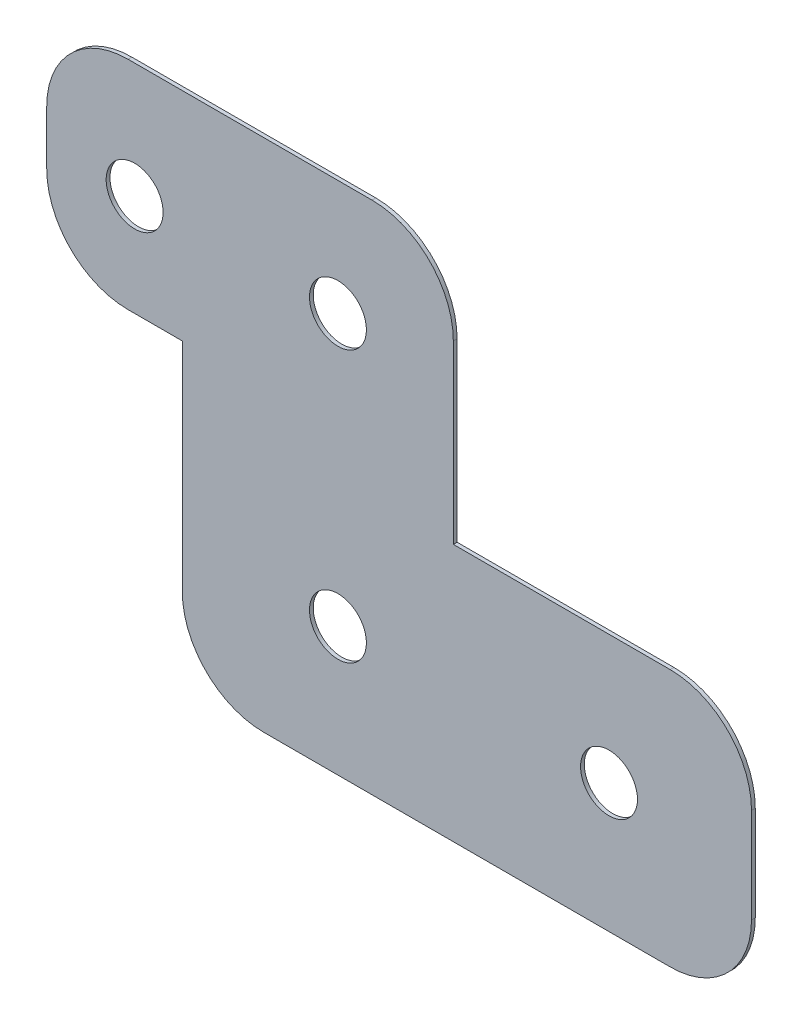
SolidWorks part; units mm, degrees
ref_plane "Front Plane" through (0, 0, 0) normal (0, 0, 1) x (1, 0, 0)
ref_plane "Top Plane" through (0, 0, 0) normal (0, 1, 0) x (1, 0, 0)
ref_plane "Right Plane" through (0, 0, 0) normal (1, 0, 0) x (0, 0, -1)
sketch "Sketch1" plane through (0, 0, 0) normal (0, 0, 1) x (1, 0, 0)
  line L1 (-460, 380) -> (60, 380)
  line L2 (-460, 380) -> (-460, 0)
  line L3 (-460, 0) -> (60, 0)
  line L4 (60, 380) -> (60, 0)
  point P5 (0, 0)
  dimension "D1" = 520
  dimension "D2" = 380
extrude "Boss-Extrude1" add sketch "Sketch1" along normal blind 2.7781
sketch "Sketch2" plane through (0, 0, 2.7781) normal (0, 0, 1) x (1, 0, 0)
  line L1 (60, 380) -> (-160, 380)
  line L2 (60, 380) -> (60, 190)
  line L3 (60, 190) -> (-160, 190)
  line L4 (-160, 380) -> (-160, 190)
  dimension "D1" = 220
  dimension "D2" = 190
sketch "Sketch3" plane through (0, 0, 2.7781) normal (0, 0, 1) x (1, 0, 0)
  line L1 (-460, 0) -> (-360, 0)
  line L2 (-460, 0) -> (-460, 220)
  line L3 (-460, 220) -> (-360, 220)
  line L4 (-360, 0) -> (-360, 220)
  dimension "D1" = 100
  dimension "D2" = 220
extrude "Cut-Extrude1" cut sketch "Sketch2" against normal blind 2.7781
extrude "Cut-Extrude2" cut sketch "Sketch3" against normal blind 2.7781
sketch "Sketch4" plane through (0, 0, 2.7781) normal (0, 0, 1) x (1, 0, 0)
  line L0 (-160, 380) -> (-460, 380) construction
  circle A0 centre (-395.1389, 295) radius 21
  circle A1 centre (-245.1389, 295) radius 21
  circle A2 centre (-245.1389, 95) radius 21
  circle A3 centre (-45.1389, 95) radius 21
  point P10 (-255.6947, 95)
  point P11 (-397.095, 295)
  point P12 (-40.4872, 95)
  point P13 (-395.1389, 295)
  point P14 (-245.1389, 95)
  dimension "D1" = 200
  dimension "D3" = 150
  dimension "D4" = 200
  dimension "D2" = 85
fillet "Fillet2" radius 60 2 edges at (-460, 220, 1.3891) (-460, 380, 1.3891)
fillet "Fillet3" radius 60 4 edges at (-160, 380, 1.3891) (60, 190, 1.3891) (60, 0, 1.3891) (-360, 0, 1.3891)
extrude "Cut-Extrude3" cut sketch "Sketch4" against normal blind 2.7781
